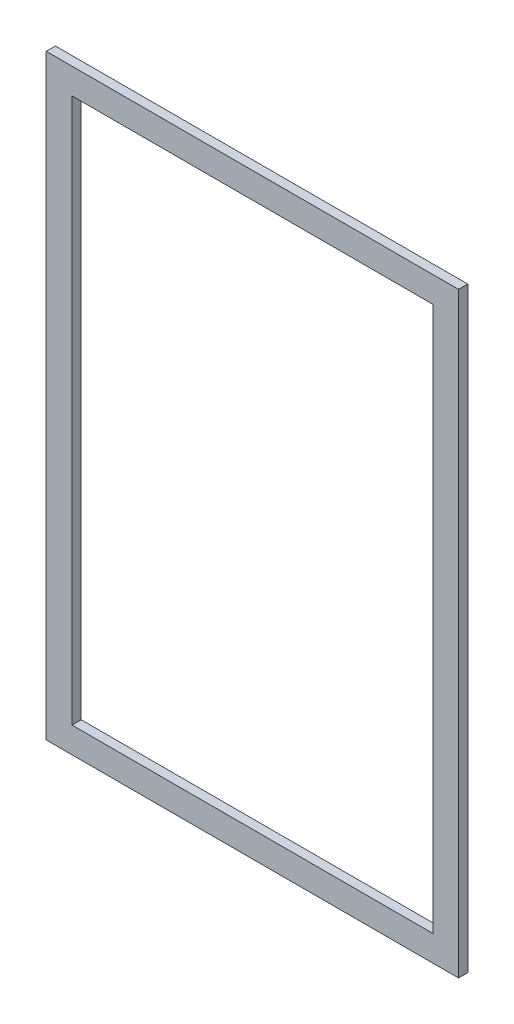
SolidWorks part; units mm, degrees
ref_plane "Front Plane" through (0, 0, 0) normal (0, 0, 1) x (1, 0, 0)
ref_plane "Top Plane" through (0, 0, 0) normal (0, 1, 0) x (1, 0, 0)
ref_plane "Right Plane" through (0, 0, 0) normal (1, 0, 0) x (0, 0, -1)
sketch "Sketch1" plane through (0, 0, 0) normal (0, 0, 1) x (1, 0, 0)
  line L1 (0, 0) -> (224, 0)
  line L2 (0, 0) -> (0, 324)
  line L3 (0, 324) -> (224, 324)
  line L4 (224, 0) -> (224, 324)
  line L5 (14, 14) -> (210, 14)
  line L6 (14, 14) -> (14, 310)
  line L7 (14, 310) -> (210, 310)
  line L8 (210, 14) -> (210, 310)
  dimension "D1" = 14
  dimension "D2" = 210
  dimension "D3" = 224
  dimension "D4" = 14
  dimension "D5" = 310
  dimension "D6" = 324
extrude "Profile" add sketch "Sketch1" along normal blind 5
equation "\"Profile_Depth\" = 5mm"
equation "\"D1@Profile\" = \"Profile_Depth\""
equation "\"EnvelopeWidth\" = 224mm"
equation "\"EnvelopeHeight\" = 324mm"
